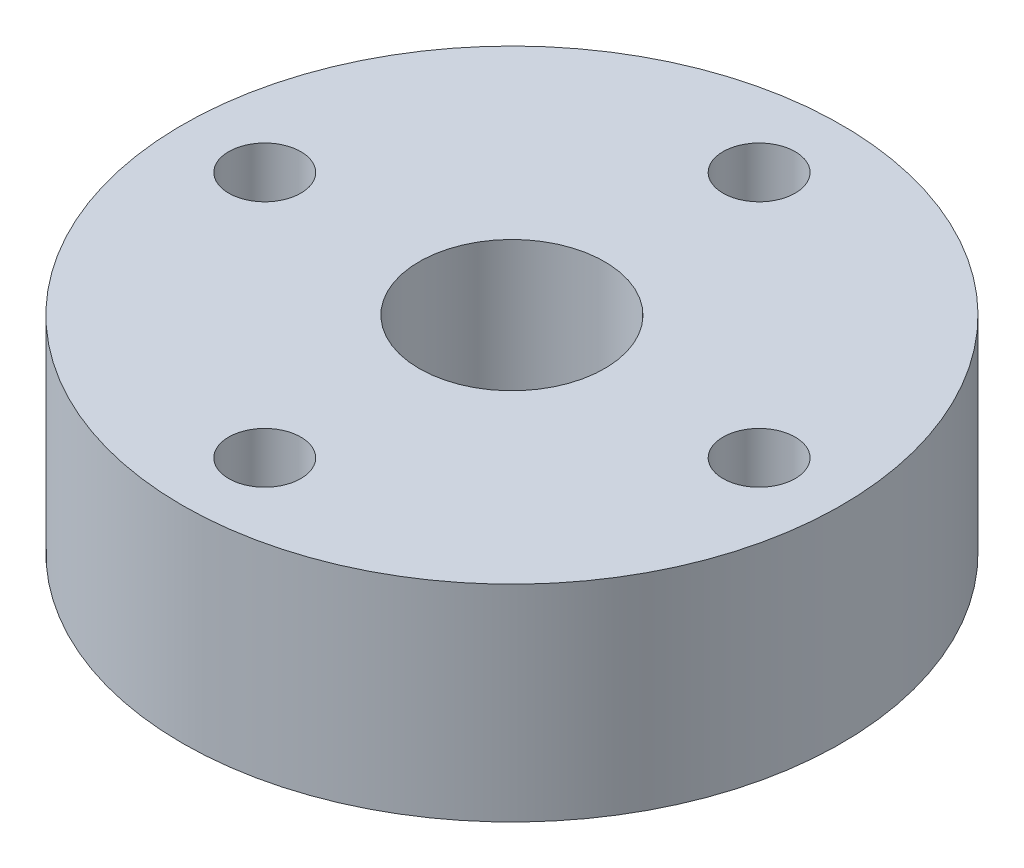
SolidWorks part; units mm, degrees
ref_plane "Front Plane" through (0, 0, 0) normal (0, 0, 1) x (1, 0, 0)
ref_plane "Top Plane" through (0, 0, 0) normal (0, 1, 0) x (1, 0, 0)
ref_plane "Right Plane" through (0, 0, 0) normal (1, 0, 0) x (0, 0, -1)
sketch "Sketch2" plane through (0, 0, 0) normal (0, 1, 0) x (1, 0, 0)
  circle A0 centre (0, 0) radius 16
  circle A1 centre (0, 0) radius 12
  circle A2 centre (0, 0) radius 4.5
  circle A3 centre (0, 12) radius 1.75
  circle A4 centre (-12, 0) radius 1.75
  circle A5 centre (0, -12) radius 1.75
  circle A6 centre (12, 0) radius 1.75
extrude "Boss-Extrude1" add sketch "Sketch2" along normal blind 10 contours A0 A6 A1 A5 A4 A3 | A6 A1 A3 A4 A5 A2
